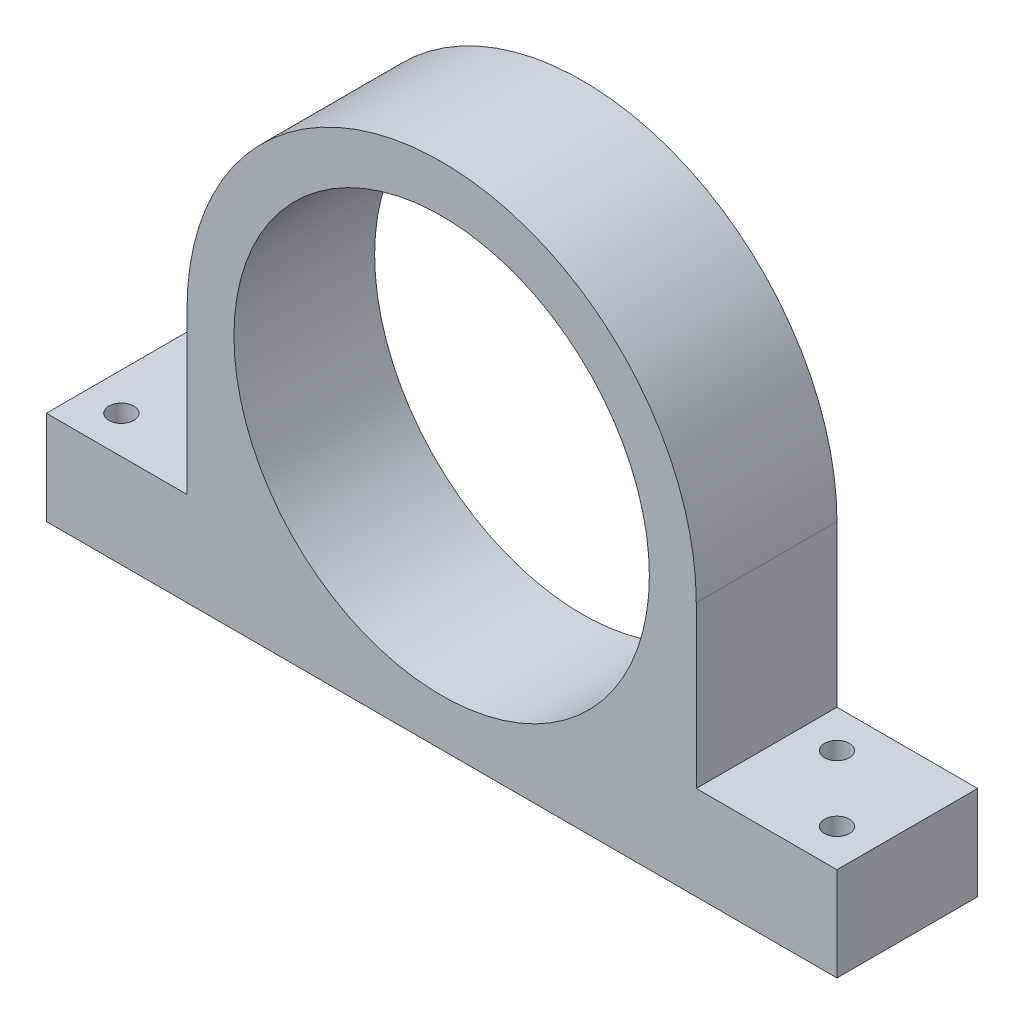
SolidWorks part; units mm, degrees
ref_plane "Front Plane" through (0, 0, 0) normal (0, 0, 1) x (1, 0, 0)
ref_plane "Top Plane" through (0, 0, 0) normal (0, 1, 0) x (1, 0, 0)
ref_plane "Right Plane" through (0, 0, 0) normal (1, 0, 0) x (0, 0, -1)
sketch "Sketch2" plane through (0, 0, 0) normal (0, 0, 1) x (1, 0, 0)
  line L0 (-27.5806, 27.5806) -> (-27.5806, 10.16)
  line L1 (27.5806, 27.5806) -> (27.5806, 10.16)
  line L2 (42.8206, 0) -> (-42.8206, 0)
  line L3 (-42.8206, 0) -> (-42.8206, 10.16)
  line L4 (-42.8206, 10.16) -> (-27.5806, 10.16)
  line L5 (42.8206, 0) -> (42.8206, 10.16)
  line L6 (42.8206, 10.16) -> (27.5806, 10.16)
  arc A0 (27.5806, 27.5806) -> (-27.5806, 27.5806) centre (0, 27.5806) ccw
  circle A1 centre (0, 27.5806) radius 22.5006
  point P10 (0, 0)
  dimension "D1" = 45.0012
  dimension "D2" = 5.08
  dimension "D3" = 10.16
  dimension "D4" = 10.16
  dimension "D5" = 17.4206
  dimension "D6" = 15.24
extrude "Boss-Extrude1" add sketch "Sketch2" along normal mid plane 15.24
hole_wizard "Tap Drill for #6-32 Tap1" positions "Sketch4" profile "Sketch5" hole size "#6-32" standard "ANSI Inch" end condition through all
sketch "Sketch4" plane through (0, 10.16, 0) normal (0, 1, 0) x (1, 0, 0)
  line L0 (-27.5806, -7.62) -> (-42.8206, -7.62) construction
  line L1 (-42.8206, -7.62) -> (-42.8206, 7.62) construction
  line L2 (-27.5806, 7.62) -> (-42.8206, 7.62) construction
  line L3 (-27.5806, -7.62) -> (-27.5806, 7.62) construction
  line L4 (42.8206, 7.62) -> (27.5806, 7.62) construction
  line L5 (27.5806, -7.62) -> (27.5806, 7.62) construction
  line L6 (42.8206, -7.62) -> (27.5806, -7.62) construction
  line L7 (42.8206, -7.62) -> (42.8206, 7.62) construction
  point P0 (-38.7566, -3.556)
  point P2 (-31.6446, 3.556)
  point P4 (31.6446, 3.556)
  point P6 (38.7566, -3.556)
  dimension "D1" = 4.064
  dimension "D2" = 4.064
  dimension "D3" = 4.064
  dimension "D4" = 4.064
  dimension "D5" = 4.064
  dimension "D6" = 4.064
  dimension "D7" = 4.064
  dimension "D8" = 4.064
sketch "Sketch5" plane through (-38.7566, 10.16, 3.556) normal (1, 0, 0) x (0, 0, 1)
  line L0 (0, 0) -> (0, 10.16)
  line L1 (0, 10.16) -> (1.3525, 10.16)
  line L2 (1.3525, 10.16) -> (1.3525, 0)
  line L5 (1.3525, 0) -> (0, 0)
  line L11 (0, -6.35) -> (0, 107.95) construction
  dimension "Thru Hole Dia." = 2.7051
  dimension "Thru Hole Depth" = 10.16
